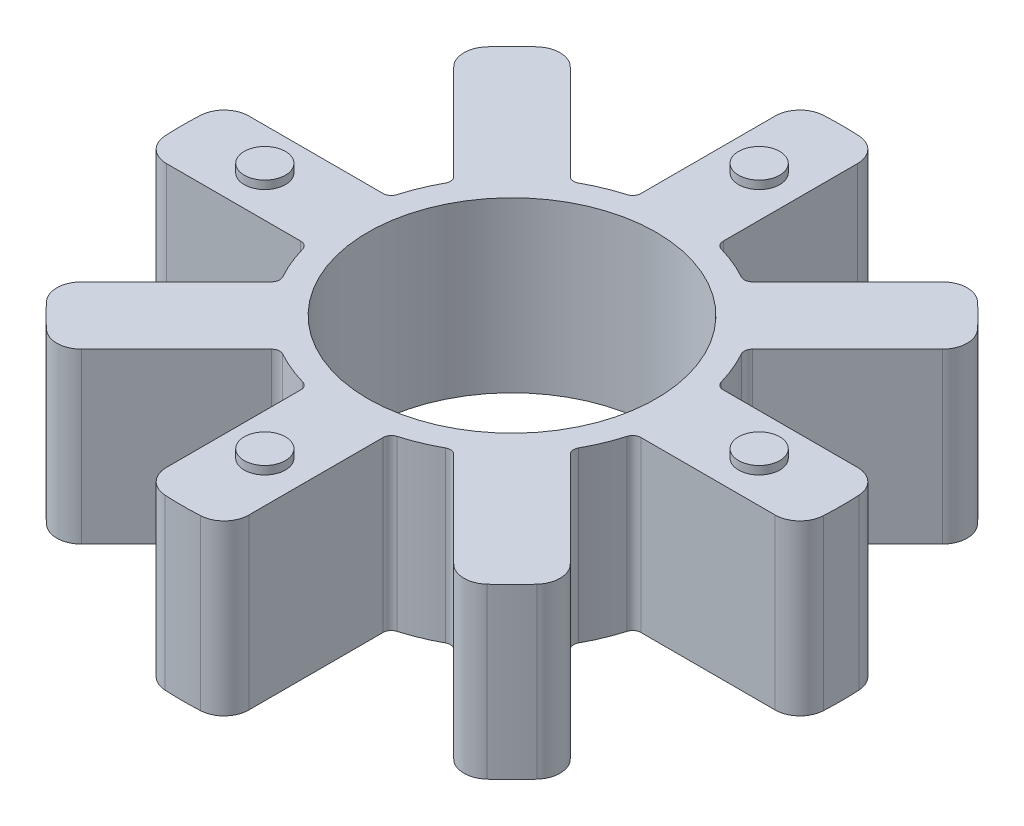
SolidWorks part; units mm, degrees
material "Rubber"
ref_plane "Front Plane" through (0, 0, 0) normal (0, 0, 1) x (1, 0, 0)
ref_plane "Top Plane" through (0, 0, 0) normal (0, 1, 0) x (1, 0, 0)
ref_plane "Right Plane" through (0, 0, 0) normal (1, 0, 0) x (0, 0, -1)
sketch "Sketch1" plane through (0, 0, 0) normal (0, 1, 0) x (1, 0, 0)
  line L0 (0, 0) -> (0, 51.2999) construction
  line L1 (5, 20.6458) -> (5, 36.9459)
  line L2 (-5, 20.6458) -> (-5, 36.9459)
  line L3 (-5, 0) -> (-5, 51.2999) construction
  line L4 (5, 0) -> (5, 51.2999) construction
  line L5 (18.1343, 11.0633) -> (29.6602, 22.5892)
  line L6 (11.0633, 18.1343) -> (22.5892, 29.6602)
  line L7 (20.6458, -5) -> (36.9459, -5)
  line L8 (20.6458, 5) -> (36.9459, 5)
  line L9 (11.0633, -18.1343) -> (22.5892, -29.6602)
  line L10 (18.1343, -11.0633) -> (29.6602, -22.5892)
  line L11 (-5, -20.6458) -> (-5, -36.9459)
  line L12 (5, -20.6458) -> (5, -36.9459)
  line L13 (-18.1343, -11.0633) -> (-29.6602, -22.5892)
  line L14 (-11.0633, -18.1343) -> (-22.5892, -29.6602)
  line L15 (-20.6458, 5) -> (-36.9459, 5)
  line L16 (-20.6458, -5) -> (-36.9459, -5)
  line L17 (-11.0633, 18.1343) -> (-22.5892, 29.6602)
  line L18 (-18.1343, 11.0633) -> (-29.6602, 22.5892)
  arc A0 (2.1622, 39.9415) -> (-2.1622, 39.9415) centre (0, 0) ccw
  circle A1 centre (0, 0) radius 30 construction
  circle A2 centre (0, 0) radius 17.5
  arc A3 (-5.7209, 19.6856) -> (-9.8745, 17.9651) centre (0, 0) ccw
  arc A4 (5, 20.6458) -> (5.7209, 19.6856) centre (6, 20.6458) ccw
  arc A5 (-5, 20.6458) -> (-5.7209, 19.6856) centre (-6, 20.6458) cw
  arc A6 (5, 36.9459) -> (2.1622, 39.9415) centre (2, 36.9459) ccw
  arc A7 (-5, 36.9459) -> (-2.1622, 39.9415) centre (-2, 36.9459) cw
  arc A8 (22.5892, 29.6602) -> (26.714, 29.7718) centre (24.7105, 27.5389) cw
  arc A9 (29.7718, 26.714) -> (26.714, 29.7718) centre (0, 0) ccw
  arc A10 (29.6602, 22.5892) -> (29.7718, 26.714) centre (27.5389, 24.7105) ccw
  arc A11 (11.0633, 18.1343) -> (9.8745, 17.9651) centre (10.3562, 18.8414) cw
  arc A12 (18.1343, 11.0633) -> (17.9651, 9.8745) centre (18.8414, 10.3562) ccw
  arc A13 (36.9459, 5) -> (39.9415, 2.1622) centre (36.9459, 2) cw
  arc A14 (39.9415, -2.1622) -> (39.9415, 2.1622) centre (0, 0) ccw
  arc A15 (36.9459, -5) -> (39.9415, -2.1622) centre (36.9459, -2) ccw
  arc A16 (20.6458, 5) -> (19.6856, 5.7209) centre (20.6458, 6) cw
  arc A17 (20.6458, -5) -> (19.6856, -5.7209) centre (20.6458, -6) ccw
  arc A18 (29.6602, -22.5892) -> (29.7718, -26.714) centre (27.5389, -24.7105) cw
  arc A19 (26.714, -29.7718) -> (29.7718, -26.714) centre (0, 0) ccw
  arc A20 (22.5892, -29.6602) -> (26.714, -29.7718) centre (24.7105, -27.5389) ccw
  arc A21 (18.1343, -11.0633) -> (17.9651, -9.8745) centre (18.8414, -10.3562) cw
  arc A22 (11.0633, -18.1343) -> (9.8745, -17.9651) centre (10.3562, -18.8414) ccw
  arc A23 (5, -36.9459) -> (2.1622, -39.9415) centre (2, -36.9459) cw
  arc A24 (-2.1622, -39.9415) -> (2.1622, -39.9415) centre (0, 0) ccw
  arc A25 (-5, -36.9459) -> (-2.1622, -39.9415) centre (-2, -36.9459) ccw
  arc A26 (5, -20.6458) -> (5.7209, -19.6856) centre (6, -20.6458) cw
  arc A27 (-5, -20.6458) -> (-5.7209, -19.6856) centre (-6, -20.6458) ccw
  arc A28 (-22.5892, -29.6602) -> (-26.714, -29.7718) centre (-24.7105, -27.5389) cw
  arc A29 (-29.7718, -26.714) -> (-26.714, -29.7718) centre (0, 0) ccw
  arc A30 (-29.6602, -22.5892) -> (-29.7718, -26.714) centre (-27.5389, -24.7105) ccw
  arc A31 (-11.0633, -18.1343) -> (-9.8745, -17.9651) centre (-10.3562, -18.8414) cw
  arc A32 (-18.1343, -11.0633) -> (-17.9651, -9.8745) centre (-18.8414, -10.3562) ccw
  arc A33 (-36.9459, -5) -> (-39.9415, -2.1622) centre (-36.9459, -2) cw
  arc A34 (-39.9415, 2.1622) -> (-39.9415, -2.1622) centre (0, 0) ccw
  arc A35 (-36.9459, 5) -> (-39.9415, 2.1622) centre (-36.9459, 2) ccw
  arc A36 (-20.6458, -5) -> (-19.6856, -5.7209) centre (-20.6458, -6) cw
  arc A37 (-20.6458, 5) -> (-19.6856, 5.7209) centre (-20.6458, 6) ccw
  arc A38 (-29.6602, 22.5892) -> (-29.7718, 26.714) centre (-27.5389, 24.7105) cw
  arc A39 (-26.714, 29.7718) -> (-29.7718, 26.714) centre (0, 0) ccw
  arc A40 (-22.5892, 29.6602) -> (-26.714, 29.7718) centre (-24.7105, 27.5389) ccw
  arc A41 (-18.1343, 11.0633) -> (-17.9651, 9.8745) centre (-18.8414, 10.3562) cw
  arc A42 (-11.0633, 18.1343) -> (-9.8745, 17.9651) centre (-10.3562, 18.8414) ccw
  arc A43 (-17.9651, 9.8745) -> (-19.6856, 5.7209) centre (0, 0) ccw
  arc A44 (9.8745, 17.9651) -> (5.7209, 19.6856) centre (0, 0) ccw
  arc A45 (19.6856, 5.7209) -> (17.9651, 9.8745) centre (0, 0) ccw
  arc A46 (17.9651, -9.8745) -> (19.6856, -5.7209) centre (0, 0) ccw
  arc A47 (5.7209, -19.6856) -> (9.8745, -17.9651) centre (0, 0) ccw
  arc A48 (-9.8745, -17.9651) -> (-5.7209, -19.6856) centre (0, 0) ccw
  arc A49 (-19.6856, -5.7209) -> (-17.9651, -9.8745) centre (0, 0) ccw
  point P107 (0, 0)
  dimension "D1" = 80
  dimension "D2" = 60
  dimension "D3" = 5
  dimension "D5" = 35
  dimension "D6" = 41
  dimension "D7" = 1
  dimension "D8" = 3
  dimension "D4" = 5
  dimension "D9" = 8
extrude "Boss-Extrude1" add sketch "Sketch1" along normal blind 20.5
sketch "Sketch2" plane through (0, 20.5, 0) normal (0, 1, 0) x (1, 0, 0)
  circle A0 centre (0, 0) radius 30 construction
  circle A1 centre (0, 30) radius 2.5
  circle A2 centre (30, 0) radius 2.5
  circle A3 centre (0, -30) radius 2.5
  circle A4 centre (-30, 0) radius 2.5
  point P14 (0, 0)
  dimension "D1" = 60
  dimension "D2" = 5
  dimension "D3" = 4
extrude "Boss-Extrude2" add sketch "Sketch2" along normal blind 1
sketch "Sketch3" plane through (0, 0, 0) normal (0, -1, 0) x (1, 0, 0)
  line L0 (-21.2132, 21.2132) -> (0, 0) construction
  line L1 (0, 0) -> (0, 30) construction
  circle A0 centre (0, 0) radius 30 construction
  circle A1 centre (-21.2132, 21.2132) radius 2.3941
  circle A2 centre (21.2132, 21.2132) radius 2.3941
  circle A3 centre (21.2132, -21.2132) radius 2.3941
  circle A4 centre (-21.2132, -21.2132) radius 2.3941
  point P15 (0, 0)
  dimension "D1" = 60
  dimension "D2" = 45
  dimension "D3" = 4
extrude "Boss-Extrude3" add sketch "Sketch3" along normal blind 1
